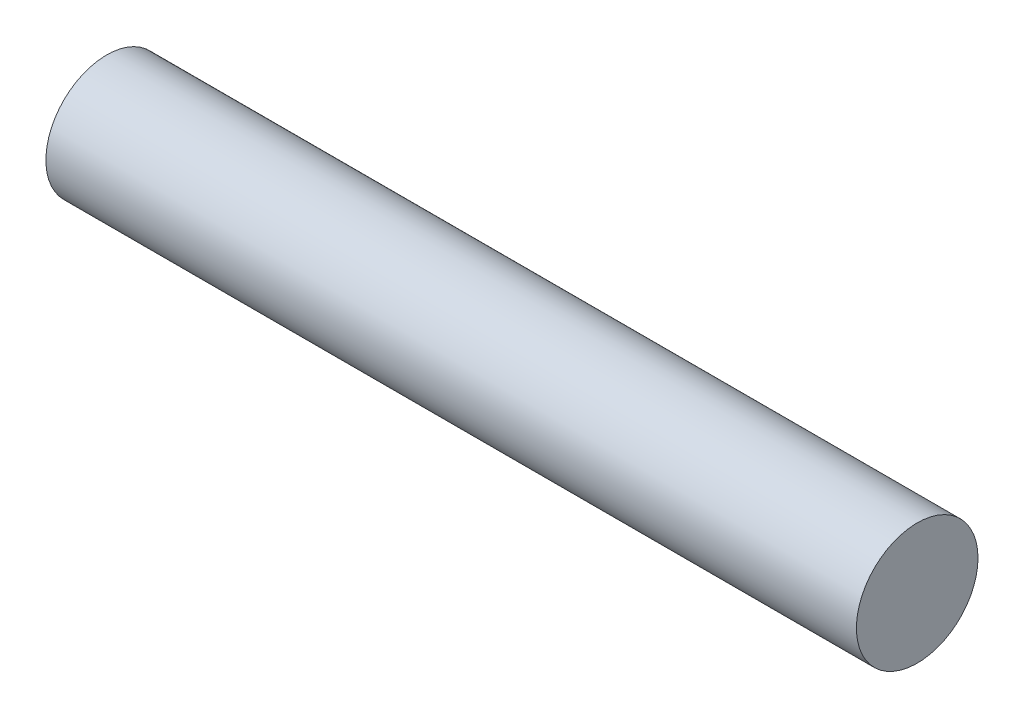
SolidWorks part; units mm, degrees
ref_plane "Front Plane" through (0, 0, 0) normal (0, 0, 1) x (1, 0, 0)
ref_plane "Top Plane" through (0, 0, 0) normal (0, 1, 0) x (1, 0, 0)
ref_plane "Right Plane" through (0, 0, 0) normal (1, 0, 0) x (0, 0, -1)
sketch "Sketch1" plane through (0, 0, 0) normal (1, 0, 0) x (0, 0, -1)
  circle A0 centre (0, 0) radius 0.75
  dimension "D1" = 1.5
extrude "Boss-Extrude1" add sketch "Sketch1" along normal blind 10
